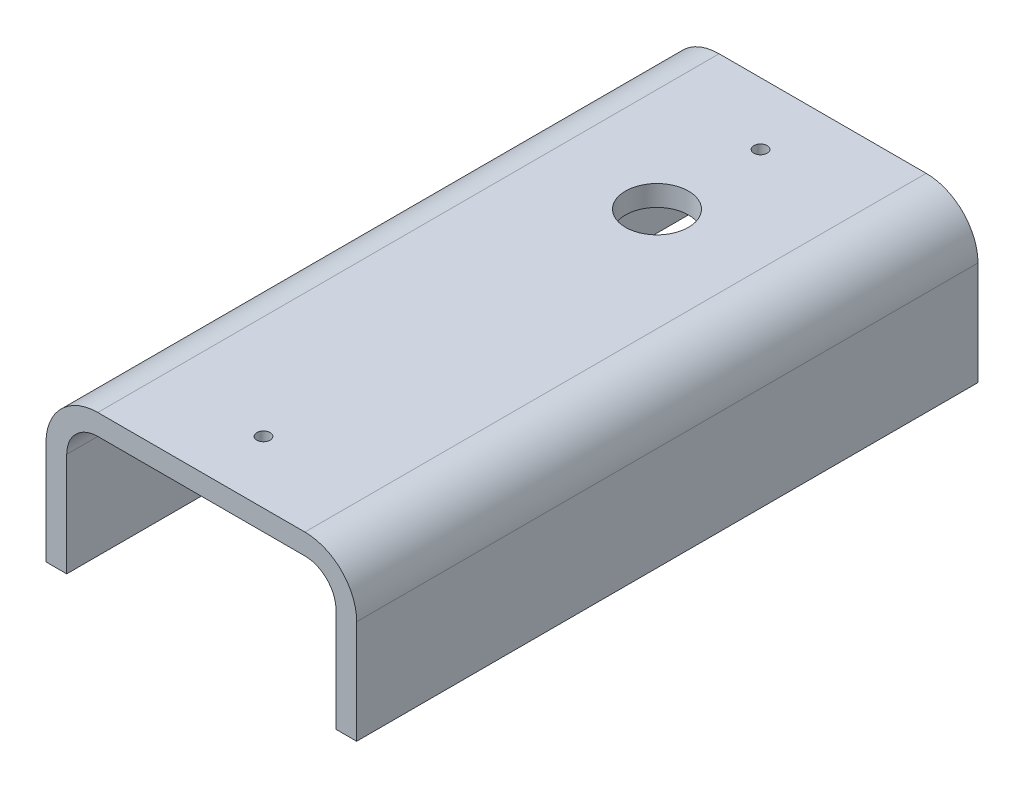
SolidWorks part; units mm, degrees
ref_plane "Front Plane" through (0, 0, 0) normal (1, 0, 0) x (0, 1, 0)
ref_plane "Top Plane" through (0, 0, 0) normal (0, 0, 1) x (0, 1, 0)
ref_plane "Right Plane" through (0, 0, 0) normal (0, 1, 0) x (-1, 0, 0)
sketch "Sketch1" plane through (0, 0, 0) normal (0, 0, 1) x (0, 1, 0)
  line L0 (-18.75, 32.5) -> (6.25, 32.5)
  line L1 (-18.75, -37.5) -> (6.25, -37.5)
  line L2 (-18.75, -37.5) -> (-18.75, 37.5)
  line L3 (-18.75, 37.5) -> (6.25, 37.5)
  line L4 (18.75, -25) -> (18.75, 25)
  line L5 (-18.75, -37.5) -> (18.75, 37.5) construction
  line L6 (-18.75, 37.5) -> (18.75, -37.5) construction
  line L7 (13.75, -25) -> (13.75, 25)
  line L8 (-18.75, -32.5) -> (6.25, -32.5)
  arc A0 (6.25, -37.5) -> (18.75, -25) centre (6.25, -25) ccw
  arc A1 (6.25, 37.5) -> (18.75, 25) centre (6.25, 25) cw
  arc A2 (6.25, 32.5) -> (13.75, 25) centre (6.25, 25) cw
  arc A3 (6.25, -32.5) -> (13.75, -25) centre (6.25, -25) ccw
  point P0 (0, 0)
  dimension "D3" = 12.5
  dimension "D1" = 37.5
  dimension "D2" = 75
  dimension "D4" = 5
extrude "Boss-Extrude1" add sketch "Sketch1" along normal blind 150 contours A3 L8 L2 L1 A0 L4 A1 L3 L0 A2 L7
sketch "Sketch2" plane through (0, 18.75, 0) normal (0, 1, 0) x (-1, 0, 0)
  line L0 (0, 150) -> (0, 0) construction
  line L1 (-25, 150) -> (25, 150) construction
  line L2 (-25, 0) -> (25, 0) construction
  circle A0 centre (0, 135) radius 1.6
  circle A1 centre (0, 15) radius 1.6
  point P5 (0, 135)
  point P6 (0, 15)
  dimension "D3" = 3.2
  dimension "D1" = 15
  dimension "D2" = 15
extrude "Cut-Extrude1" cut sketch "Sketch2" against normal through all
sketch "Sketch4" plane through (0, 18.75, 0) normal (0, 1, 0) x (-1, 0, 0)
  line L0 (-25, 0) -> (25, 0) construction
  line L1 (37.5, 150) -> (37.5, 0) construction
  circle A0 centre (0, 40) radius 7.6
  dimension "D1" = 40
  dimension "D2" = 15.2
  dimension "D3" = 37.5
extrude "Cut-Extrude2" cut sketch "Sketch4" against normal through all
